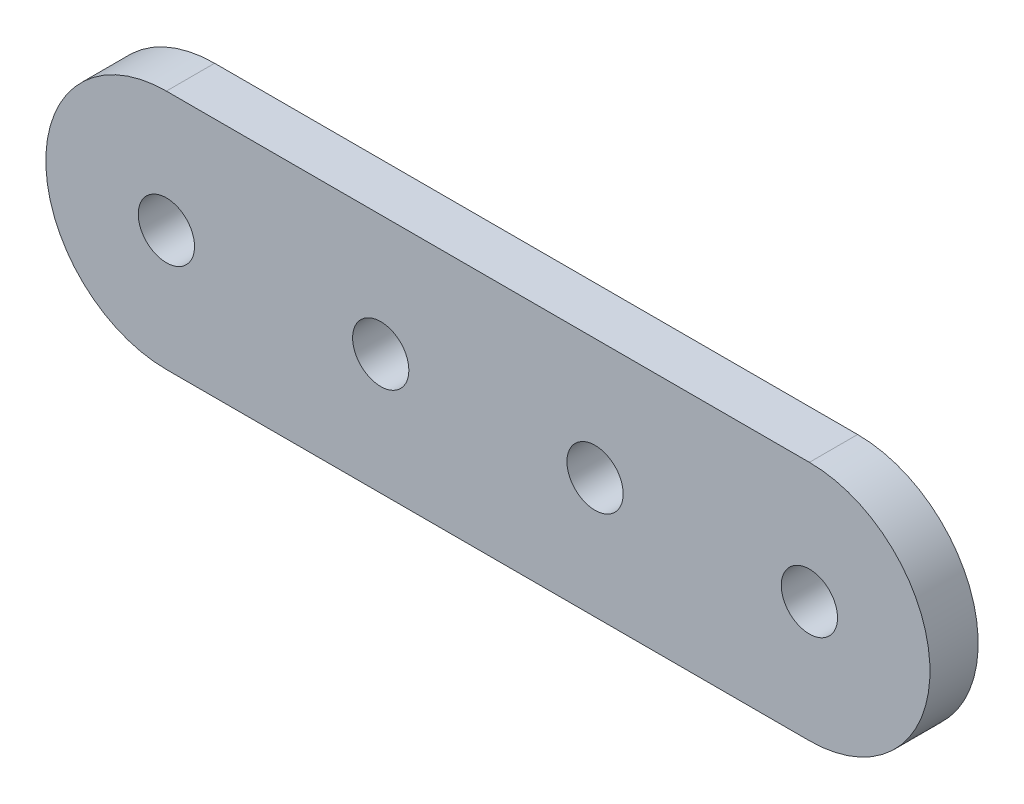
SolidWorks part; units mm, degrees
ref_plane "前基準面" through (0, 0, 0) normal (0, 0, 1) x (1, 0, 0)
ref_plane "上基準面" through (0, 0, 0) normal (0, 1, 0) x (1, 0, 0)
ref_plane "右基準面" through (0, 0, 0) normal (1, 0, 0) x (0, 0, -1)
sketch "草圖1" plane through (0, 0, 0) normal (0, 0, 1) x (1, 0, 0)
  line L0 (-20, 0) -> (-6.6667, 0) construction
  line L1 (-20, 7.5) -> (20, 7.5)
  line L2 (-6.6667, 0) -> (6.6667, 0) construction
  line L3 (-20, -7.5) -> (20, -7.5)
  line L4 (6.6667, 0) -> (20, 0) construction
  line L5 (-20, 7.5) -> (20, -7.5) construction
  line L6 (-20, -7.5) -> (20, 7.5) construction
  arc A0 (20, 7.5) -> (20, -7.5) centre (20, 0) cw
  arc A1 (-20, 7.5) -> (-20, -7.5) centre (-20, 0) ccw
  circle A2 centre (-20, 0) radius 1.75
  circle A3 centre (20, 0) radius 1.75
  circle A4 centre (-6.6667, 0) radius 1.75
  circle A5 centre (6.6667, 0) radius 1.75
  point P0 (0, 0)
  dimension "D3" = 3.5
  dimension "D1" = 15
  dimension "D2" = 40
extrude "伸長1" add sketch "草圖1" along normal blind 3
